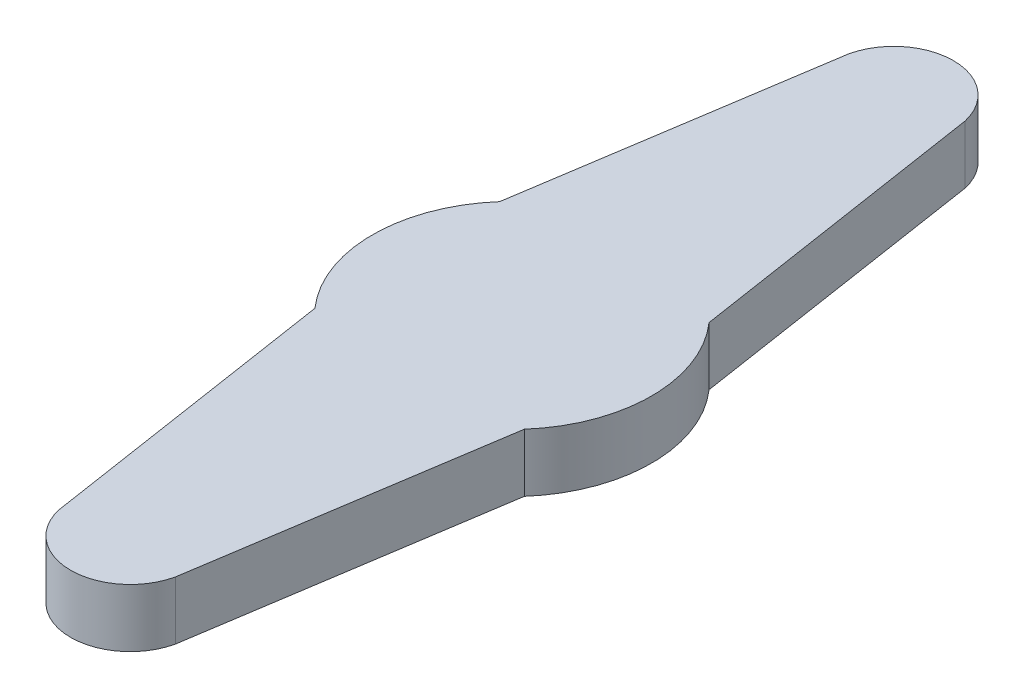
SolidWorks part; units mm, degrees
ref_plane "Front Plane" through (0, 0, 0) normal (0, 0, 1) x (1, 0, 0)
ref_plane "Top Plane" through (0, 0, 0) normal (0, 1, 0) x (1, 0, 0)
ref_plane "Right Plane" through (0, 0, 0) normal (1, 0, 0) x (0, 0, -1)
sketch "Sketch1" plane through (0, 0, 0) normal (0, 1, 0) x (1, 0, 0)
  line L0 (0, -20.8655) -> (0, 20.8655) construction
  line L1 (-2.5, 16.9686) -> (-4.5, 3.9686)
  line L2 (2.5, 16.9686) -> (4.5, 3.9686)
  line L3 (-6.6, 0) -> (6.6, 0) construction
  line L4 (-2.5, -16.9686) -> (-4.5, -3.9686)
  line L5 (2.5, -16.9686) -> (4.5, -3.9686)
  arc A0 (-4.5, 3.9686) -> (-4.5, -3.9686) centre (0, 0) ccw
  arc A1 (-2.5, 16.9686) -> (2.5, 16.9686) centre (0, 16.4061) cw
  arc A2 (-2.5, -16.9686) -> (2.5, -16.9686) centre (0, -16.4061) ccw
  arc A3 (4.5, -3.9686) -> (4.5, 3.9686) centre (0, 0) ccw
  point P8 (0, 18.9686)
  point P11 (-4.4819, 3.9891)
  point P12 (-4.2509, 4.2344)
  point P13 (-4.3604, 4.1215)
  dimension "D1" = 12
  dimension "D2" = 5
  dimension "D3" = 15
  dimension "D4" = 2
  dimension "D5" = 9
extrude "Boss-Extrude1" add sketch "Sketch1" along normal blind 2.5 contours L2 A3 L5 A2 L4 A0 L1 A1
